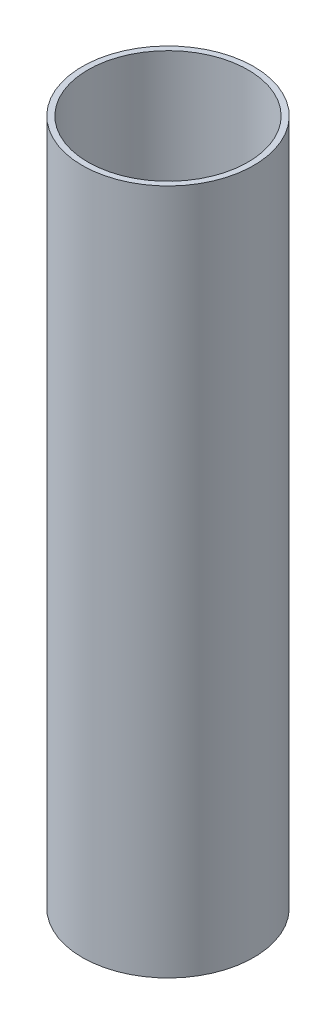
SolidWorks part; units mm, degrees
ref_plane "前视基准面" through (0, 0, 0) normal (0, 0, 1) x (1, 0, 0)
ref_plane "上视基准面" through (0, 0, 0) normal (0, 1, 0) x (1, 0, 0)
ref_plane "右视基准面" through (0, 0, 0) normal (1, 0, 0) x (0, 0, -1)
other "Configuration Table"
sketch "草图1" plane through (0, 0, 0) normal (0, 1, 0) x (1, 0, 0)
  circle A0 centre (0, 0) radius 60
  dimension "D1" = 120
extrude "凸台-拉伸1" add sketch "草图1" along normal mid plane 480
shell "抽壳3" thickness 4
